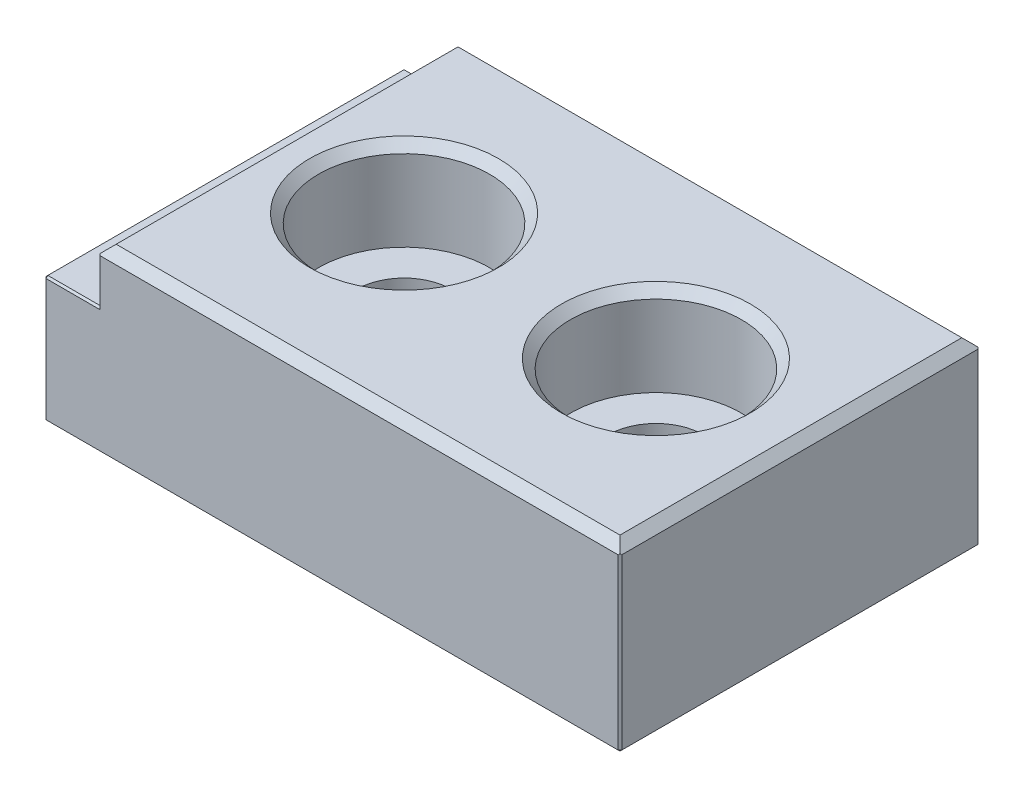
SolidWorks part; units mm, degrees
material "6061 Alloy"
ref_plane "Front Plane" through (0, 0, 0) normal (0, 0, 1) x (1, 0, 0)
ref_plane "Top Plane" through (0, 0, 0) normal (0, 1, 0) x (1, 0, 0)
ref_plane "Right Plane" through (0, 0, 0) normal (1, 0, 0) x (0, 0, -1)
sketch "Sketch1" plane through (0, 0, 0) normal (0, 1, 0) x (1, 0, 0)
  line L0 (-4.1336, 14.25) -> (-4.1336, -5.75) construction
  line L1 (-14.1336, 14.25) -> (17.8664, 14.25)
  line L2 (-14.1336, 14.25) -> (-14.1336, -5.75)
  line L3 (-14.1336, -5.75) -> (17.8664, -5.75)
  line L4 (17.8664, 14.25) -> (17.8664, -5.75)
  line L5 (9.8664, 14.25) -> (9.8664, -5.75) construction
  circle A0 centre (-4.1336, 4.25) radius 1.5
  circle A1 centre (9.8664, 4.25) radius 1.5
  dimension "D1" = 32
  dimension "D2" = 20
  dimension "D3" = 10
  dimension "D4" = 8
extrude "Boss-Extrude1" add sketch "Sketch1" along normal blind 10
hole_wizard "CBORE for M5 SHCS1" positions "Sketch5" profile "Sketch4" counterbore size "M5" standard "ANSI Metric" end condition through all
sketch "Sketch5" plane through (0, 10, 0) normal (0, 1, 0) x (1, 0, 0)
  point P0 (-4.1336, 4.25)
  point P3 (9.8664, 4.25)
sketch "Sketch4" plane through (-4.1336, 10, -4.25) normal (1, 0, 0) x (0, 0, 1)
  line L0 (0, 0) -> (0, 10)
  line L1 (0, 10) -> (2.65, 10)
  line L3 (2.65, 10) -> (2.65, 5)
  line L4 (2.65, 5) -> (4.75, 5)
  line L5 (4.75, 5) -> (4.75, 0)
  line L7 (4.75, 0) -> (0, 0)
  line L11 (0, -6.35) -> (0, 107.95) construction
  dimension "Thru Hole Dia." = 5.3
  dimension "Thru Hole Depth" = 10
  dimension "C'Bore Dia." = 9.5
  dimension "C'Bore Depth" = 5
sketch "Sketch7" plane through (0, 10, 0) normal (0, 1, 0) x (1, 0, 0)
  line L0 (17.8664, 14.25) -> (-14.1336, 14.25) construction
  line L1 (-14.1336, -5.75) -> (-11.1336, -5.75)
  line L2 (-14.1336, -5.75) -> (-14.1336, 14.25)
  line L3 (-14.1336, 14.25) -> (-11.1336, 14.25)
  line L4 (-11.1336, -5.75) -> (-11.1336, 14.25)
  dimension "D1" = 3
extrude "Cut-Extrude1" cut sketch "Sketch7" against normal blind 3
chamfer "Chamfer1" distance 0.5 angle 45 6 edges at (9.8664, 10, 0.5) (-4.1336, 10, 0.5) (-11.1336, 10, -4.25) (3.3664, 10, 5.75) (17.8664, 10, -4.25) (3.3664, 10, -14.25)
chamfer "Chamfer2" distance 0.1 angle 45 15 edges at (1.8664, 0, 5.75) (-11.1336, 8.25, 5.75) (-14.1336, 3.5, 5.75) (-12.6336, 7, 5.75) (-14.1336, 0, -4.25) (-14.1336, 7, -4.25) (-11.1336, 8.25, -14.25) (-12.6336, 7, -14.25) (-14.1336, 3.5, -14.25) (1.8664, 0, -14.25) (17.8664, 4.75, 5.75) (17.8664, 0, -4.25) (17.8664, 4.75, -14.25) (-4.1336, 0, -1.6) (9.8664, 0, -1.6)
